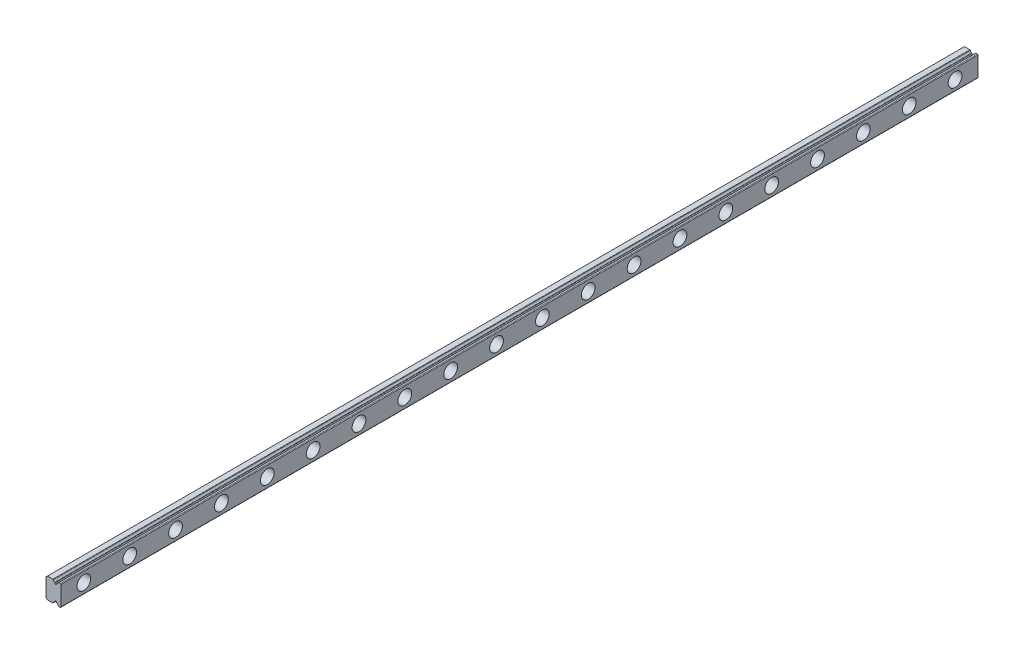
SolidWorks part; units mm, degrees
material "AISI 304"
ref_plane "前视基准面" through (0, 0, 0) normal (0, 0, 1) x (1, 0, 0)
ref_plane "上视基准面" through (0, 0, 0) normal (0, 1, 0) x (1, 0, 0)
ref_plane "右视基准面" through (0, 0, 0) normal (1, 0, 0) x (0, 0, -1)
sketch "草图1" plane through (0, 0, 0) normal (0, 0, 1) x (1, 0, 0)
  line L0 (0, 8.4) -> (0.6, 9)
  line L1 (0.6, 0) -> (2.9423, 0)
  line L2 (0, 0.6) -> (0, 8.4)
  line L3 (0.6, 9) -> (2.9423, 9)
  line L4 (6.5, 0.3) -> (6.5, 8.7)
  line L5 (0, 0.6) -> (0.6, 0)
  line L6 (4.25, 9) -> (4.25, 8) construction
  line L7 (4.25, 9) -> (4.25, 9.3) construction
  line L8 (3.85, 8) -> (3.85, 8.0351)
  line L9 (4.65, 8) -> (4.65, 8.0351)
  line L10 (5.5577, 9) -> (6.2, 9)
  line L11 (6.5, 4.5) -> (0, 4.5) construction
  line L12 (3.85, 8) -> (3.85, 8.0351)
  line L13 (4.65, 8) -> (4.65, 8.0351)
  line L14 (4.25, 0) -> (4.25, -0.3) construction
  line L15 (4.25, 0) -> (4.25, 1) construction
  line L16 (4.65, 1) -> (4.65, 0.9649)
  line L17 (3.85, 1) -> (3.85, 0.9649)
  line L18 (4.65, 1) -> (4.65, 0.9649)
  line L19 (3.85, 1) -> (3.85, 0.9649)
  line L20 (5.5577, 0) -> (6.2, 0)
  arc A0 (3.85, 8) -> (4.65, 8) centre (4.25, 8) ccw
  arc A1 (3.1291, 8.8714) -> (3.7357, 8.2158) centre (4.25, 9.3) ccw
  arc A2 (4.7643, 8.2158) -> (5.3709, 8.8714) centre (4.25, 9.3) ccw
  arc A3 (5.3709, 8.8714) -> (5.5577, 9) centre (5.5577, 8.8) cw
  arc A4 (4.65, 8.0351) -> (4.7643, 8.2158) centre (4.85, 8.0351) cw
  arc A5 (3.85, 8.0351) -> (3.7357, 8.2158) centre (3.65, 8.0351) ccw
  arc A6 (3.1291, 8.8714) -> (2.9423, 9) centre (2.9423, 8.8) ccw
  arc A7 (3.1291, 8.8714) -> (2.9423, 9) centre (2.9423, 8.8) ccw
  arc A8 (5.3709, 8.8714) -> (5.5577, 9) centre (5.5577, 8.8) cw
  arc A9 (4.65, 8.0351) -> (4.7643, 8.2158) centre (4.85, 8.0351) cw
  arc A10 (3.85, 8.0351) -> (3.7357, 8.2158) centre (3.65, 8.0351) ccw
  arc A11 (3.7357, 8.2158) -> (3.1291, 8.8714) centre (4.25, 9.3) cw
  arc A12 (5.3709, 8.8714) -> (4.7643, 8.2158) centre (4.25, 9.3) cw
  arc A13 (5.3709, 0.1286) -> (5.5577, 0) centre (5.5577, 0.2) ccw
  arc A14 (3.1291, 0.1286) -> (2.9423, 0) centre (2.9423, 0.2) cw
  arc A15 (5.3709, 0.1286) -> (4.7643, 0.7842) centre (4.25, -0.3) ccw
  arc A16 (3.7357, 0.7842) -> (3.1291, 0.1286) centre (4.25, -0.3) ccw
  arc A17 (3.85, 0.9649) -> (3.7357, 0.7842) centre (3.65, 0.9649) cw
  arc A18 (4.65, 0.9649) -> (4.7643, 0.7842) centre (4.85, 0.9649) ccw
  arc A19 (3.85, 0.9649) -> (3.7357, 0.7842) centre (3.65, 0.9649) cw
  arc A20 (4.65, 0.9649) -> (4.7643, 0.7842) centre (4.85, 0.9649) ccw
  arc A21 (4.7643, 0.7842) -> (5.3709, 0.1286) centre (4.25, -0.3) cw
  arc A22 (3.1291, 0.1286) -> (3.7357, 0.7842) centre (4.25, -0.3) cw
  arc A23 (3.85, 1) -> (4.65, 1) centre (4.25, 1) cw
  arc A24 (6.2, 0) -> (6.5, 0.3) centre (6.2, 0.3) ccw
  arc A25 (6.2, 9) -> (6.5, 8.7) centre (6.2, 8.7) cw
  point P0 (0, 0)
  point P2 (0, 9)
  point P24 (5.4119, 9)
  point P27 (4.65, 8.1686)
  point P49 (4.65, 0.8314)
  point P50 (5.4119, 0)
  point P53 (6.5, 0)
  dimension "D3" = 1
  dimension "D7" = 0.8
  dimension "D9" = 2.4
  dimension "D10" = 0.2
  dimension "D11" = 0.3
  dimension "D1" = 6.5
  dimension "D2" = 9
  dimension "D4" = 2.25
  dimension "D8" = 0.3
extrude "凸台-拉伸1" add sketch "草图1" along normal blind 400 contours A25 L10 A3 A2 A4 L9 A0 L8 A5 A1 A6 L3 L0 L2 L5 L1 A14 A16 A17 L17 A23 L16 A18 A15 A13 L20 A24 L4
sketch "草图2" plane through (6.5, 0, 0) normal (1, 0, 0) x (0, 0, -1)
  line L0 (-400, 4.5) -> (-390, 4.5) construction
  line L1 (-400, 0.3) -> (-400, 8.7) construction
  line L2 (-390, 4.5) -> (-10, 4.5) construction
  line L3 (-10, 4.5) -> (0, 4.5) construction
  line L4 (0, 0.3) -> (0, 8.7) construction
  line L5 (-10, 4.5) -> (-30, 4.5) construction
  circle A0 centre (-10, 4.5) radius 3
  circle A1 centre (-30, 4.5) radius 3
  circle A2 centre (-50, 4.5) radius 3
  circle A3 centre (-70, 4.5) radius 3
  circle A4 centre (-90, 4.5) radius 3
  circle A5 centre (-110, 4.5) radius 3
  circle A6 centre (-130, 4.5) radius 3
  circle A7 centre (-150, 4.5) radius 3
  circle A8 centre (-170, 4.5) radius 3
  circle A9 centre (-190, 4.5) radius 3
  circle A10 centre (-210, 4.5) radius 3
  circle A11 centre (-230, 4.5) radius 3
  circle A12 centre (-250, 4.5) radius 3
  circle A13 centre (-270, 4.5) radius 3
  circle A14 centre (-290, 4.5) radius 3
  circle A15 centre (-310, 4.5) radius 3
  circle A16 centre (-330, 4.5) radius 3
  circle A17 centre (-350, 4.5) radius 3
  circle A18 centre (-370, 4.5) radius 3
  circle A19 centre (-390, 4.5) radius 3
  circle A20 centre (-410, 4.5) radius 3
  circle A21 centre (-430, 4.5) radius 3
  circle A22 centre (-450, 4.5) radius 3
  circle A23 centre (-470, 4.5) radius 3
  circle A24 centre (-490, 4.5) radius 3
  circle A25 centre (-510, 4.5) radius 3
  circle A26 centre (-530, 4.5) radius 3
  circle A27 centre (-550, 4.5) radius 3
  circle A28 centre (-570, 4.5) radius 3
  circle A29 centre (-590, 4.5) radius 3
  circle A30 centre (-610, 4.5) radius 3
  circle A31 centre (-630, 4.5) radius 3
  circle A32 centre (-650, 4.5) radius 3
  circle A33 centre (-670, 4.5) radius 3
  circle A34 centre (-690, 4.5) radius 3
  circle A35 centre (-710, 4.5) radius 3
  circle A36 centre (-730, 4.5) radius 3
  circle A37 centre (-750, 4.5) radius 3
  circle A38 centre (-770, 4.5) radius 3
  circle A39 centre (-790, 4.5) radius 3
  circle A40 centre (-810, 4.5) radius 3
  circle A41 centre (-830, 4.5) radius 3
  circle A42 centre (-850, 4.5) radius 3
  circle A43 centre (-870, 4.5) radius 3
  circle A44 centre (-890, 4.5) radius 3
  circle A45 centre (-910, 4.5) radius 3
  circle A46 centre (-930, 4.5) radius 3
  circle A47 centre (-950, 4.5) radius 3
  circle A48 centre (-970, 4.5) radius 3
  circle A49 centre (-990, 4.5) radius 3
  circle A50 centre (-1010, 4.5) radius 3
  circle A51 centre (-1030, 4.5) radius 3
  circle A52 centre (-1050, 4.5) radius 3
  circle A53 centre (-1070, 4.5) radius 3
  circle A54 centre (-1090, 4.5) radius 3
  circle A55 centre (-1110, 4.5) radius 3
  circle A56 centre (-1130, 4.5) radius 3
  circle A57 centre (-1150, 4.5) radius 3
  circle A58 centre (-1170, 4.5) radius 3
  circle A59 centre (-1190, 4.5) radius 3
  circle A60 centre (-1210, 4.5) radius 3
  circle A61 centre (-1230, 4.5) radius 3
  circle A62 centre (-1250, 4.5) radius 3
  circle A63 centre (-1270, 4.5) radius 3
  circle A64 centre (-1290, 4.5) radius 3
  circle A65 centre (-1310, 4.5) radius 3
  circle A66 centre (-1330, 4.5) radius 3
  circle A67 centre (-1350, 4.5) radius 3
  circle A68 centre (-1370, 4.5) radius 3
  circle A69 centre (-1390, 4.5) radius 3
  circle A70 centre (-1410, 4.5) radius 3
  circle A71 centre (-1430, 4.5) radius 3
  circle A72 centre (-1450, 4.5) radius 3
  circle A73 centre (-1470, 4.5) radius 3
  circle A74 centre (-1490, 4.5) radius 3
  circle A75 centre (-1510, 4.5) radius 3
  circle A76 centre (-1530, 4.5) radius 3
  circle A77 centre (-1550, 4.5) radius 3
  circle A78 centre (-1570, 4.5) radius 3
  circle A79 centre (-1590, 4.5) radius 3
  circle A80 centre (-1610, 4.5) radius 3
  circle A81 centre (-1630, 4.5) radius 3
  circle A82 centre (-1650, 4.5) radius 3
  circle A83 centre (-1670, 4.5) radius 3
  circle A84 centre (-1690, 4.5) radius 3
  circle A85 centre (-1710, 4.5) radius 3
  circle A86 centre (-1730, 4.5) radius 3
  circle A87 centre (-1750, 4.5) radius 3
  circle A88 centre (-1770, 4.5) radius 3
  circle A89 centre (-1790, 4.5) radius 3
  circle A90 centre (-1810, 4.5) radius 3
  circle A91 centre (-1830, 4.5) radius 3
  circle A92 centre (-1850, 4.5) radius 3
  circle A93 centre (-1870, 4.5) radius 3
  circle A94 centre (-1890, 4.5) radius 3
  circle A95 centre (-1910, 4.5) radius 3
  circle A96 centre (-1930, 4.5) radius 3
  circle A97 centre (-1950, 4.5) radius 3
  circle A98 centre (-1970, 4.5) radius 3
  circle A99 centre (-1990, 4.5) radius 3
  circle A100 centre (-2010, 4.5) radius 3
  circle A101 centre (-2030, 4.5) radius 3
  circle A102 centre (-2050, 4.5) radius 3
  circle A103 centre (-2070, 4.5) radius 3
  circle A104 centre (-2090, 4.5) radius 3
  circle A105 centre (-2110, 4.5) radius 3
  circle A106 centre (-2130, 4.5) radius 3
  circle A107 centre (-2150, 4.5) radius 3
  circle A108 centre (-2170, 4.5) radius 3
  circle A109 centre (-2190, 4.5) radius 3
  circle A110 centre (-2210, 4.5) radius 3
  circle A111 centre (-2230, 4.5) radius 3
  circle A112 centre (-2250, 4.5) radius 3
  circle A113 centre (-2270, 4.5) radius 3
  circle A114 centre (-2290, 4.5) radius 3
  circle A115 centre (-2310, 4.5) radius 3
  circle A116 centre (-2330, 4.5) radius 3
  circle A117 centre (-2350, 4.5) radius 3
  circle A118 centre (-2370, 4.5) radius 3
  circle A119 centre (-2390, 4.5) radius 3
  circle A120 centre (-2410, 4.5) radius 3
  circle A121 centre (-2430, 4.5) radius 3
  circle A122 centre (-2450, 4.5) radius 3
  circle A123 centre (-2470, 4.5) radius 3
  dimension "D2" = 6
  dimension "D1" = 10
  dimension "D4" = 20
  dimension "D3" = 25
  dimension "D5" = 100
extrude "切除-拉伸1" cut sketch "草图2" against normal blind 4.5
sketch "草图3" plane through (2, 0, 0) normal (1, 0, 0) x (0, 0, -1)
  line L0 (-10, 4.5) -> (-30, 4.5) construction
  circle A0 centre (-10, 4.5) radius 1.75
  circle A1 centre (-30, 4.5) radius 1.75
  circle A2 centre (-50, 4.5) radius 1.75
  circle A3 centre (-70, 4.5) radius 1.75
  circle A4 centre (-90, 4.5) radius 1.75
  circle A5 centre (-110, 4.5) radius 1.75
  circle A6 centre (-130, 4.5) radius 1.75
  circle A7 centre (-150, 4.5) radius 1.75
  circle A8 centre (-170, 4.5) radius 1.75
  circle A9 centre (-190, 4.5) radius 1.75
  circle A10 centre (-210, 4.5) radius 1.75
  circle A11 centre (-230, 4.5) radius 1.75
  circle A12 centre (-250, 4.5) radius 1.75
  circle A13 centre (-270, 4.5) radius 1.75
  circle A14 centre (-290, 4.5) radius 1.75
  circle A15 centre (-310, 4.5) radius 1.75
  circle A16 centre (-330, 4.5) radius 1.75
  circle A17 centre (-350, 4.5) radius 1.75
  circle A18 centre (-370, 4.5) radius 1.75
  circle A19 centre (-390, 4.5) radius 1.75
  circle A20 centre (-410, 4.5) radius 1.75
  circle A21 centre (-430, 4.5) radius 1.75
  circle A22 centre (-450, 4.5) radius 1.75
  circle A23 centre (-470, 4.5) radius 1.75
  circle A24 centre (-490, 4.5) radius 1.75
  circle A25 centre (-510, 4.5) radius 1.75
  circle A26 centre (-530, 4.5) radius 1.75
  circle A27 centre (-550, 4.5) radius 1.75
  circle A28 centre (-570, 4.5) radius 1.75
  circle A29 centre (-590, 4.5) radius 1.75
  circle A30 centre (-610, 4.5) radius 1.75
  circle A31 centre (-630, 4.5) radius 1.75
  circle A32 centre (-650, 4.5) radius 1.75
  circle A33 centre (-670, 4.5) radius 1.75
  circle A34 centre (-690, 4.5) radius 1.75
  circle A35 centre (-710, 4.5) radius 1.75
  circle A36 centre (-730, 4.5) radius 1.75
  circle A37 centre (-750, 4.5) radius 1.75
  circle A38 centre (-770, 4.5) radius 1.75
  circle A39 centre (-790, 4.5) radius 1.75
  circle A40 centre (-810, 4.5) radius 1.75
  circle A41 centre (-830, 4.5) radius 1.75
  circle A42 centre (-850, 4.5) radius 1.75
  circle A43 centre (-870, 4.5) radius 1.75
  circle A44 centre (-890, 4.5) radius 1.75
  circle A45 centre (-910, 4.5) radius 1.75
  circle A46 centre (-930, 4.5) radius 1.75
  circle A47 centre (-950, 4.5) radius 1.75
  circle A48 centre (-970, 4.5) radius 1.75
  circle A49 centre (-990, 4.5) radius 1.75
  circle A50 centre (-1010, 4.5) radius 1.75
  circle A51 centre (-1030, 4.5) radius 1.75
  circle A52 centre (-1050, 4.5) radius 1.75
  circle A53 centre (-1070, 4.5) radius 1.75
  dimension "D1" = 3.5
  dimension "D3" = 20
  dimension "D2" = 25
  dimension "D4" = 30
extrude "切除-拉伸2" cut sketch "草图3" against normal through all
